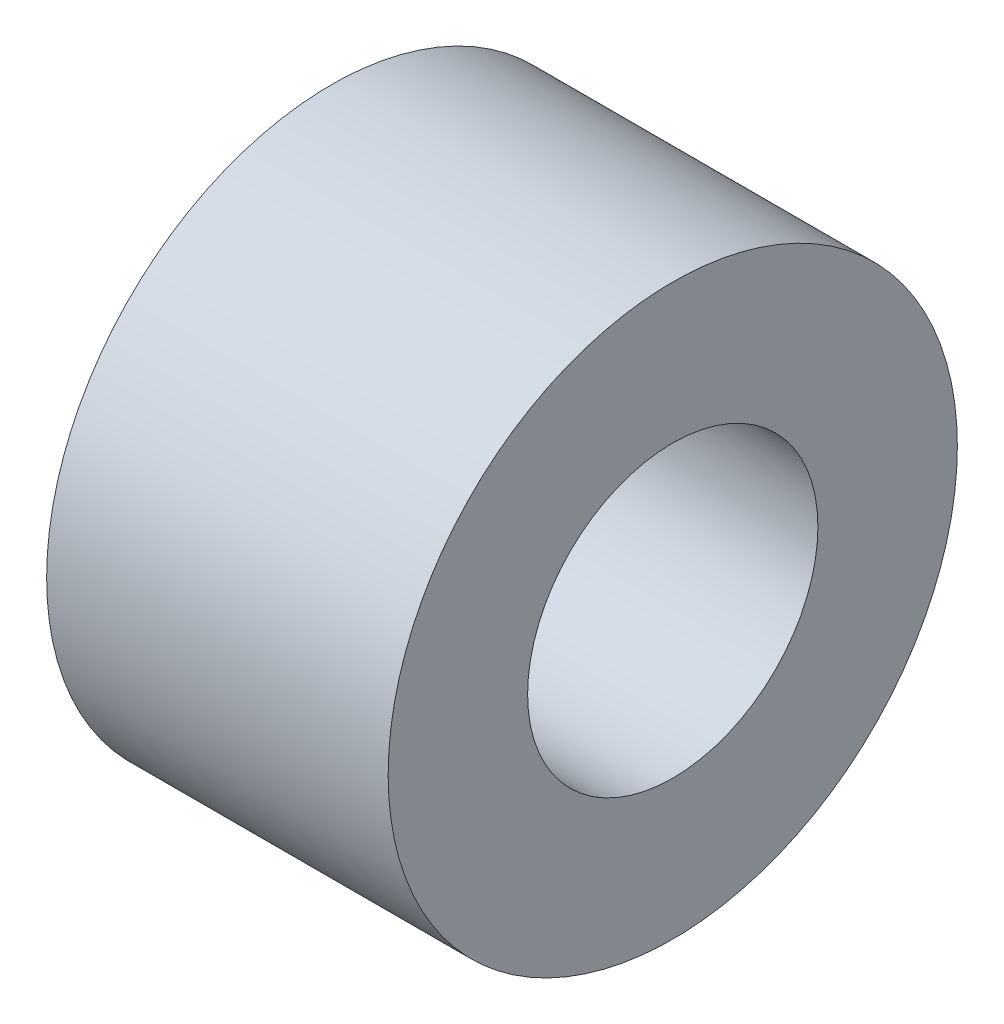
SolidWorks part; units mm, degrees
ref_plane "Front Plane" through (0, 0, 0) normal (0, 0, 1) x (1, 0, 0)
ref_plane "Top Plane" through (0, 0, 0) normal (0, 1, 0) x (1, 0, 0)
ref_plane "Right Plane" through (0, 0, 0) normal (1, 0, 0) x (0, 0, -1)
sketch "Sketch1" plane through (0, 0, 0) normal (1, 0, 0) x (0, 0, -1)
  circle A0 centre (0, 0) radius 3.2385
  circle A1 centre (0, 0) radius 6.35
  dimension "D1" = 6.477
  dimension "D2" = 12.7
extrude "Boss-Extrude1" add sketch "Sketch1" along normal blind 7.62
